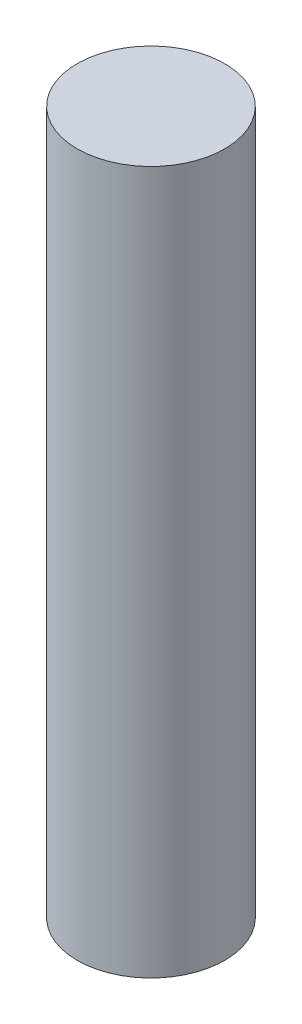
SolidWorks part; units mm, degrees
ref_plane "Front Plane" through (0, 0, 0) normal (0, 0, 1) x (1, 0, 0)
ref_plane "Top Plane" through (0, 0, 0) normal (0, 1, 0) x (1, 0, 0)
ref_plane "Right Plane" through (0, 0, 0) normal (1, 0, 0) x (0, 0, -1)
sketch "Sketch1" plane through (0, 0, 0) normal (0, 1, 0) x (1, 0, 0)
  circle A0 centre (0, 0) radius 10.668
  dimension "D1" = 21.336
extrude "Boss-Extrude1" add sketch "Sketch1" along normal blind 101.6
